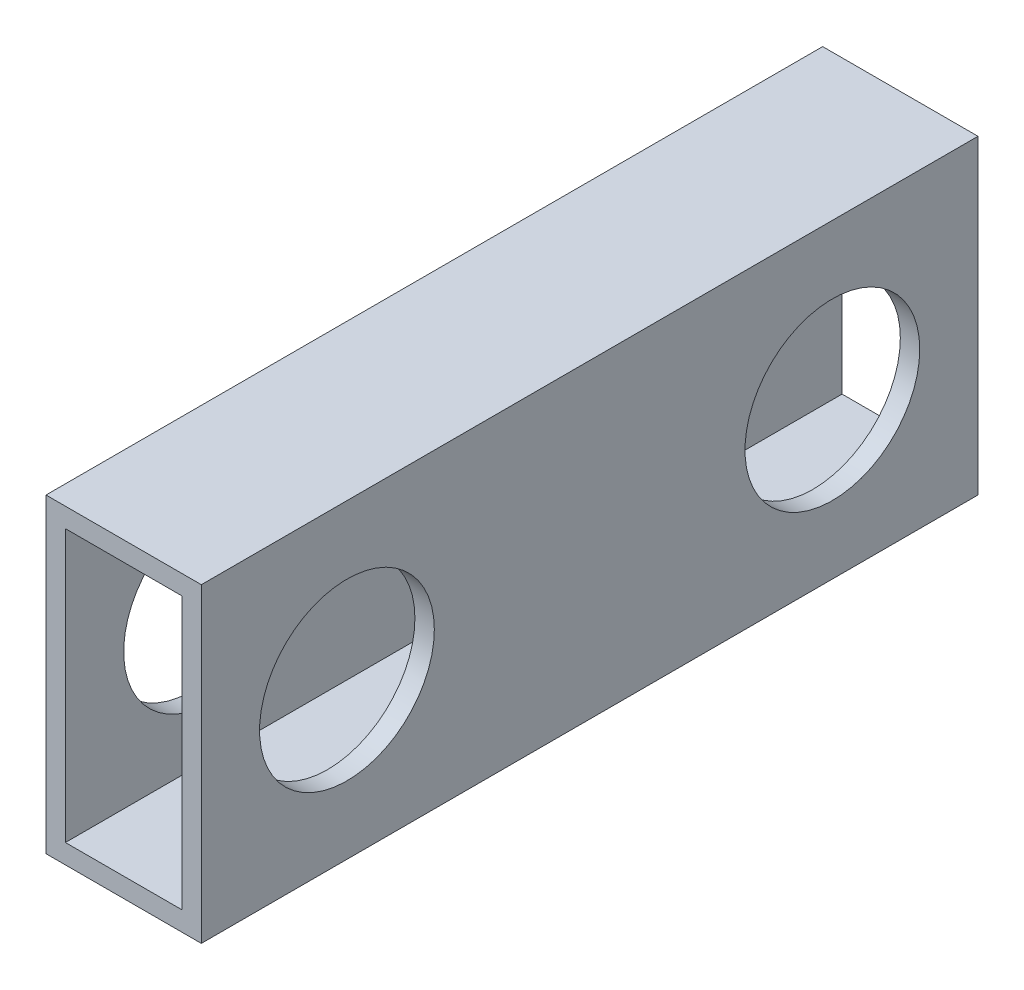
SolidWorks part; units mm, degrees
ref_plane "Front Plane" through (0, 0, 0) normal (0, 0, 1) x (1, 0, 0)
ref_plane "Top Plane" through (0, 0, 0) normal (0, 1, 0) x (1, 0, 0)
ref_plane "Right Plane" through (0, 0, 0) normal (1, 0, 0) x (0, 0, -1)
sketch "Sketch1" plane through (0, 0, 0) normal (0, 0, 1) x (1, 0, 0)
  line L1 (-12.7, 25.4) -> (12.7, 25.4)
  line L2 (-12.7, 25.4) -> (-12.7, -25.4)
  line L3 (-12.7, -25.4) -> (12.7, -25.4)
  line L4 (12.7, 25.4) -> (12.7, -25.4)
  line L5 (0, -25.4) -> (0, 25.4) construction
  line L6 (-12.7, 0) -> (12.7, 0) construction
  point P0 (0, 0)
  dimension "D1" = 25.4
  dimension "D2" = 50.8
extrude "Boss-Extrude1" add sketch "Sketch1" along normal mid plane 127
shell "Shell2" thickness 3.175
sketch "Sketch2" plane through (12.7, 0, 0) normal (1, 0, 0) x (0, 0, -1)
  line L0 (0, 0) -> (0, 50000) construction
  circle A0 centre (39.6875, 0) radius 14.2875
  circle A1 centre (-39.6875, 0) radius 14.2875
  point P2 (0, 0)
  dimension "D1" = 28.575
  dimension "D2" = 79.375
extrude "Cut-Extrude1" cut sketch "Sketch2" against normal through all
